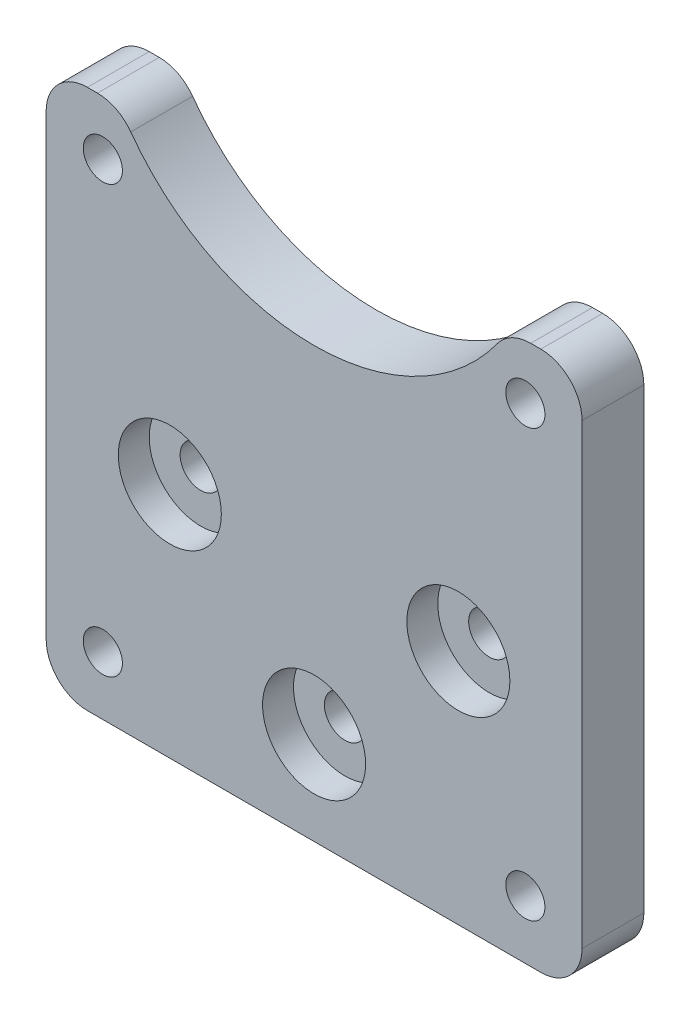
SolidWorks part; units mm, degrees
ref_plane "前视基准面" through (0, 0, 0) normal (0, 0, 1) x (1, 0, 0)
ref_plane "上视基准面" through (0, 0, 0) normal (0, 1, 0) x (1, 0, 0)
ref_plane "右视基准面" through (0, 0, 0) normal (1, 0, 0) x (0, 0, -1)
other "Configuration Table"
sketch "草图1" plane through (0, 0, 0) normal (0, 0, 1) x (1, 0, 0)
  line L0 (-51.4586, 0) -> (70.6019, 0) construction
  line L1 (-13, -8) -> (13, -8)
  line L5 (13, 18.19) -> (13, -8)
  line L6 (-13, 18.19) -> (-13, -8)
  line L7 (0, 44.2739) -> (0, -40.9926) construction
  line L8 (-13, 18.19) -> (-9.4381, 18.19)
  line L10 (9.4381, 18.19) -> (13, 18.19)
  circle A0 centre (7, 3.5) radius 1
  circle A1 centre (-7, 3.5) radius 1
  circle A2 centre (0, -3.5) radius 1
  circle A3 centre (10.25, 15.54) radius 0.95
  circle A4 centre (-10.25, 15.54) radius 0.95
  circle A5 centre (-10.25, -5.16) radius 0.95
  circle A6 centre (10.25, -5.16) radius 0.95
  arc A7 (-9.4381, 18.19) -> (9.4381, 18.19) centre (0, 23.84) ccw
  point P0 (0, 0)
  dimension "D2" = 2
  dimension "D3" = 2
  dimension "D4" = 7
  dimension "D6" = 14
  dimension "D7" = 3.5
  dimension "D9" = 1.9
  dimension "D13" = 11
  dimension "D14" = 1.9
  dimension "D15" = 1.9
  dimension "D16" = 1.9
  dimension "D5" = 26
  dimension "D8" = 8
  dimension "D10" = 20.5
  dimension "D11" = 20.7
  dimension "D12" = 8.3
extrude "凸台-拉伸1" add sketch "草图1" along normal blind 3
sketch "草图2" plane through (0, 0, 3) normal (0, 0, 1) x (1, 0, 0)
  circle A0 centre (-7, 3.5) radius 2.5
  circle A1 centre (7, 3.5) radius 2.5
  circle A2 centre (0, -3.5) radius 2.5
  dimension "D1" = 5
  dimension "D2" = 5
  dimension "D3" = 5
extrude "切除-拉伸1" cut sketch "草图2" against normal blind 1.5
fillet "圆角1" radius 2 6 edges at (-13, -8, 1.5) (13, -8, 1.5) (-13, 18.19, 1.5) (9.4381, 18.19, 1.5) (-9.4381, 18.19, 1.5) (13, 18.19, 1.5)
